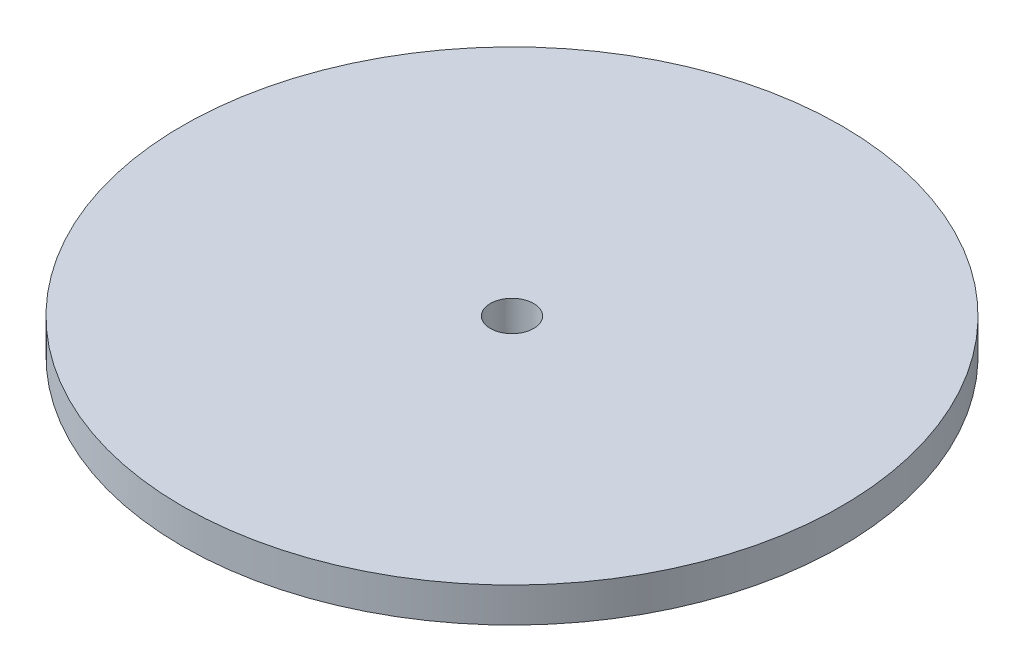
SolidWorks part; units mm, degrees
ref_plane "Front Plane" through (0, 0, 0) normal (0, 0, 1) x (1, 0, 0)
ref_plane "Top Plane" through (0, 0, 0) normal (0, 1, 0) x (1, 0, 0)
ref_plane "Right Plane" through (0, 0, 0) normal (1, 0, 0) x (0, 0, -1)
sketch "Sketch1" plane through (0, 0, 0) normal (0, 1, 0) x (1, 0, 0)
  circle A0 centre (0, 0) radius 38
  circle A1 centre (0, 0) radius 2.5
  dimension "D1" = 5
  dimension "D2" = 76
extrude "Boss-Extrude1" add sketch "Sketch1" along normal blind 4
